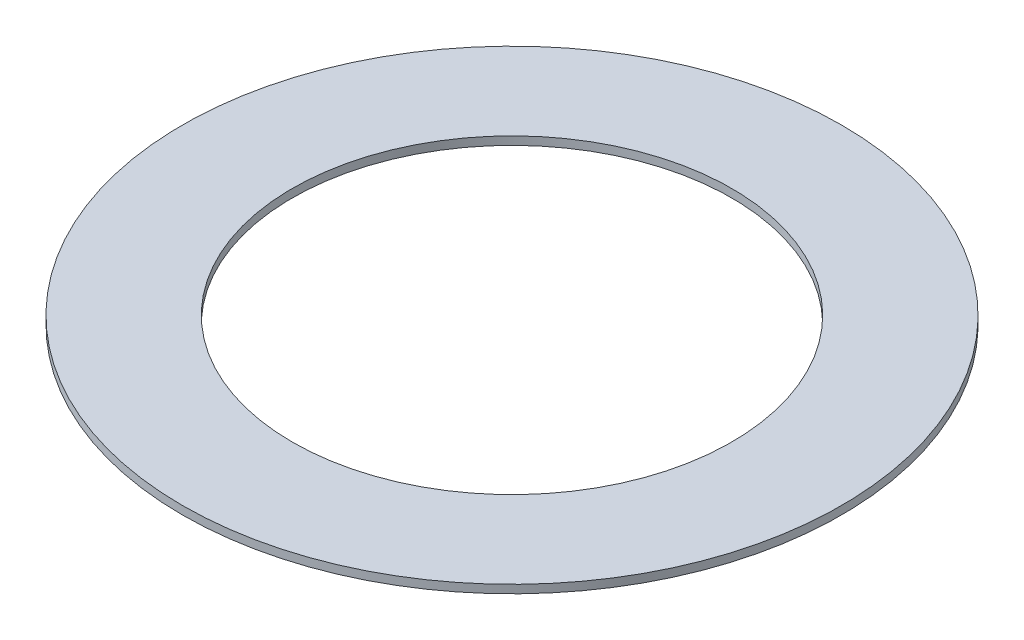
SolidWorks part; units mm, degrees
ref_plane "Front Plane" through (0, 0, 0) normal (0, 0, 1) x (1, 0, 0)
ref_plane "Top Plane" through (0, 0, 0) normal (0, 1, 0) x (1, 0, 0)
ref_plane "Right Plane" through (0, 0, 0) normal (1, 0, 0) x (0, 0, -1)
sketch "Sketch1" plane through (0, 0, 0) normal (0, 1, 0) x (1, 0, 0)
  circle A0 centre (0, 0) radius 120
  circle A1 centre (0, 0) radius 80
  dimension "D1" = 240
  dimension "D2" = 160
  dimension "D3" = 40
extrude "Boss-Extrude1" add sketch "Sketch1" along normal mid plane 3
